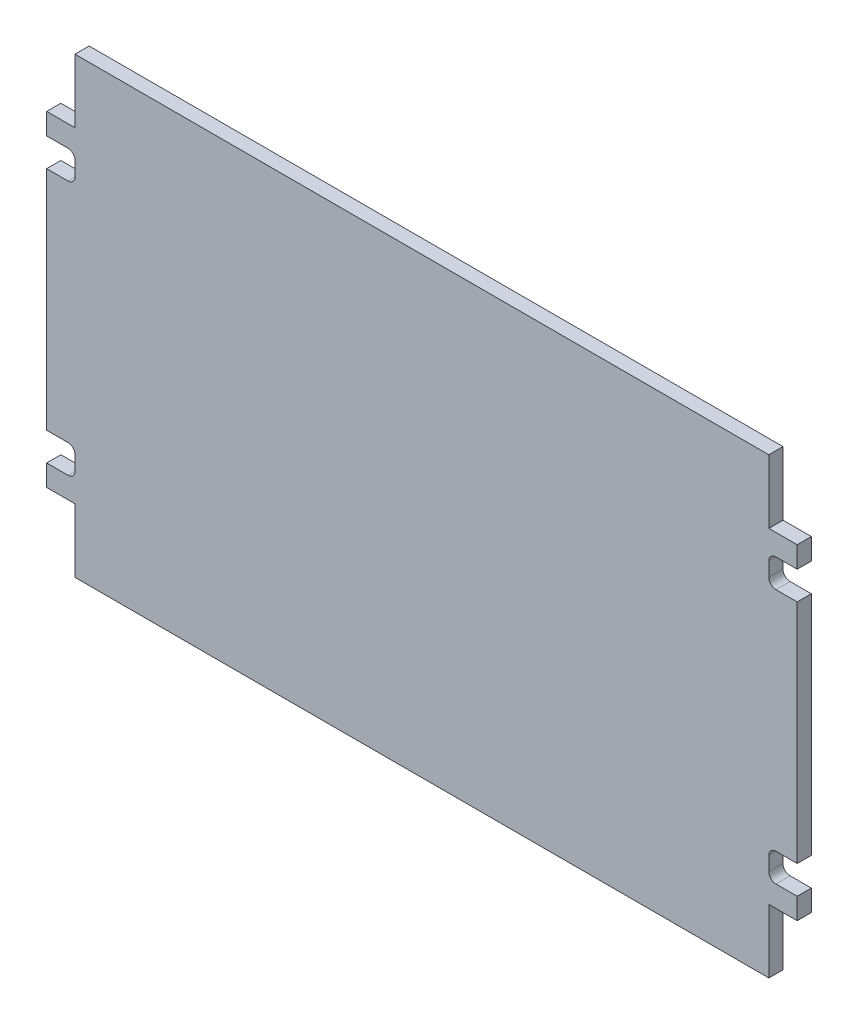
SolidWorks part; units mm, degrees
ref_plane "Ön Düzlem" through (0, 0, 0) normal (0, 0, 1) x (1, 0, 0)
ref_plane "Üst Düzlem" through (0, 0, 0) normal (0, 1, 0) x (1, 0, 0)
ref_plane "Sağ Düzlem" through (0, 0, 0) normal (1, 0, 0) x (0, 0, -1)
sketch "Sketch1" plane through (0, 0, 0) normal (0, 0, 1) x (1, 0, 0)
  line L1 (0, 0) -> (106, 0)
  line L2 (0, 0) -> (0, 64)
  line L3 (0, 64) -> (106, 64)
  line L4 (106, 0) -> (106, 64)
extrude "Boss-Extrude1" add sketch "Sketch1" along normal blind 2
sketch "Sketch2" plane through (0, 0, 2) normal (0, 0, 1) x (1, 0, 0)
  line L1 (0, 64) -> (4, 64)
  line L2 (0, 64) -> (0, 55)
  line L3 (0, 55) -> (4, 55)
  line L4 (4, 64) -> (4, 55)
  line L5 (0, 0) -> (4, 0)
  line L6 (0, 0) -> (0, 9)
  line L7 (0, 9) -> (4, 9)
  line L8 (4, 0) -> (4, 9)
  line L9 (106, 0) -> (102, 0)
  line L10 (106, 0) -> (106, 9)
  line L11 (106, 9) -> (102, 9)
  line L12 (102, 0) -> (102, 9)
  line L13 (106, 64) -> (102, 64)
  line L14 (106, 64) -> (106, 55)
  line L15 (106, 55) -> (102, 55)
  line L16 (102, 64) -> (102, 55)
  dimension "D1" = 4
  dimension "D2" = 9
  dimension "D3" = 4
  dimension "D4" = 9
  dimension "D5" = 4
  dimension "D6" = 9
  dimension "D7" = 4
  dimension "D8" = 9
extrude "Cut-Extrude1" cut sketch "Sketch2" against normal through all
sketch "Sketch3" plane through (0, 0, 2) normal (0, 0, 1) x (1, 0, 0)
  line L0 (106, 9) -> (106, 55) construction
  line L1 (106, 12) -> (103, 12)
  line L2 (106, 12) -> (106, 16)
  line L3 (106, 16) -> (103, 16)
  line L4 (102, 13) -> (102, 15)
  line L5 (106, 9) -> (102, 9) construction
  line L6 (0, 55) -> (0, 9) construction
  line L7 (4, 9) -> (0, 9) construction
  line L8 (0, 12) -> (3, 12)
  line L9 (0, 12) -> (0, 16)
  line L10 (0, 16) -> (3, 16)
  line L11 (4, 13) -> (4, 15)
  line L12 (0, 55) -> (4, 55) construction
  line L13 (0, 52) -> (3, 52)
  line L14 (0, 52) -> (0, 48)
  line L15 (0, 48) -> (3, 48)
  line L16 (4, 51) -> (4, 49)
  line L17 (102, 55) -> (106, 55) construction
  line L18 (106, 52) -> (103, 52)
  line L19 (106, 52) -> (106, 48)
  line L20 (106, 48) -> (103, 48)
  line L21 (102, 51) -> (102, 49)
  arc A0 (103, 12) -> (102, 13) centre (103, 13) cw
  arc A1 (102, 15) -> (103, 16) centre (103, 15) cw
  arc A2 (103, 48) -> (102, 49) centre (103, 49) cw
  arc A3 (102, 51) -> (103, 52) centre (103, 51) cw
  arc A4 (3, 12) -> (4, 13) centre (3, 13) ccw
  arc A5 (4, 15) -> (3, 16) centre (3, 15) ccw
  arc A6 (4, 49) -> (3, 48) centre (3, 49) cw
  arc A7 (4, 51) -> (3, 52) centre (3, 51) ccw
  point P30 (102, 12)
  point P33 (102, 16)
  point P36 (102, 48)
  point P39 (102, 52)
  point P42 (4, 12)
  point P45 (4, 16)
  point P48 (4, 48)
  point P51 (4, 52)
  dimension "D13" = 1
  dimension "D1" = 3
  dimension "D2" = 3
  dimension "D3" = 3
  dimension "D4" = 4
  dimension "D5" = 4
  dimension "D6" = 4
  dimension "D7" = 4
  dimension "D8" = 4
  dimension "D9" = 4
  dimension "D10" = 3
  dimension "D11" = 4
  dimension "D12" = 4
extrude "Cut-Extrude2" cut sketch "Sketch3" against normal through all
